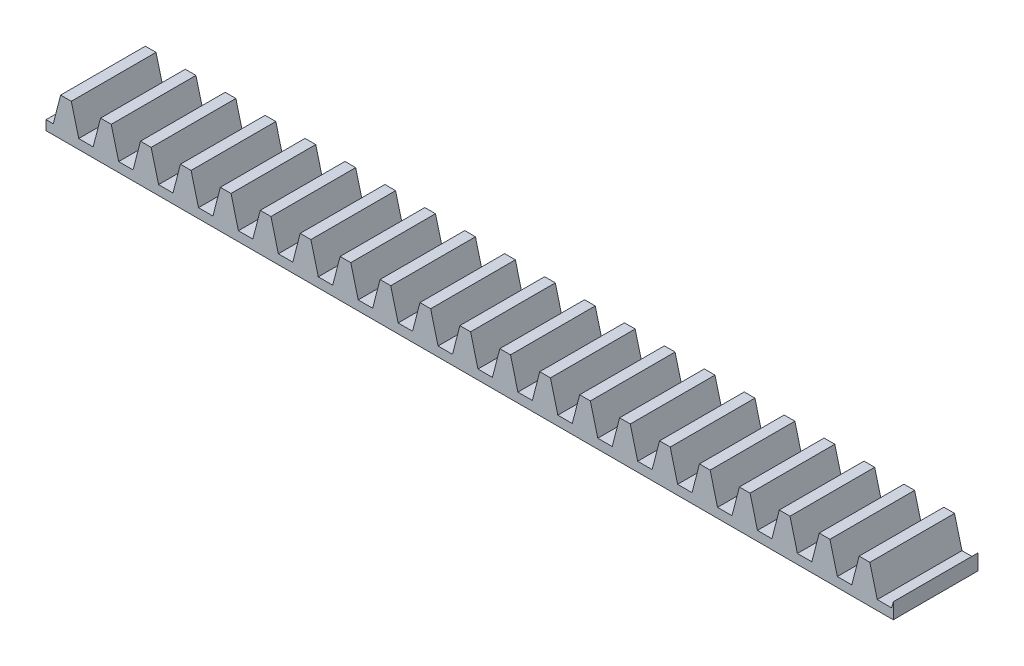
SolidWorks part; units mm, degrees
extrude "Blank" add sketch "BlankSke" against normal blind 10
sketch "BlankSke" plane through (0, 0, 0) normal (0, 0, 1) x (1, 0, 0)
  line L1 (0, 0) -> (100, 0)
  line L2 (0, 0) -> (0, 4.5)
  line L3 (0, 4.5) -> (100, 4.5)
  line L4 (100, 0) -> (100, 4.5)
  dimension "Length" = 100
  dimension "Blank_height" = 4.5
ref_plane "Plane1" through (0, 0, 0) normal (0, 0, 1) x (1, 0, 0)
ref_plane "Plane2" through (0, 0, 0) normal (0, 1, 0) x (1, 0, 0)
ref_plane "Plane3" through (0, 0, 0) normal (1, 0, 0) x (0, 0, -1)
sketch "HoldingSke" plane through (0, 0, 0) normal (0, 1, 0) x (1, 0, 0)
  line L0 (0, 0) -> (0.0928, 0.6602)
  line L1 (-15, 0) -> (100, 0) construction
  line L2 (0, 0) -> (-2.1039, 2.3779)
  line L3 (0, 0) -> (-11.863, 4.5341)
  line L4 (0, 0) -> (7.9495, 3.3743)
  line L5 (0, 0) -> (-23.7986, -8.8762)
  line L6 (0, 0) -> (-10.5278, -7.1032)
  line L9 (-67.7845, 28.3722) -> (29.0302, 53.4102)
  line L10 (-76.2, 3.8779) -> (-73.2, 3.8779)
  line L11 (0, 0) -> (-10, 0)
  line L12 (-76.2, 101.6) -> (-76.147, 101.6)
  line L13 (24.9733, 27.94) -> (52.9518, 28.4284)
  line L14 (24.9733, 27.94) -> (24.9743, 27.94)
  line L15 (24.9733, 27.94) -> (100.4006, 29.5858)
  circle A0 centre (0, 0) radius 19.05
  circle A1 centre (0, 0) radius 1.5
  circle A2 centre (0, 0) radius 12.7
  dimension "MPH" = 3
  dimension "Diameter" = 38.1
  dimension "Num_teeth" = 23
  dimension "Pitch" = 0.6667
  dimension "Show_teeth" = 998
  dimension "Thickness" = 12.7
  dimension "Ap" = 14.5
  dimension "Pitch_height" = 3
  dimension "Width" = 10
  dimension "Backlash" = 0.053
  dimension "Addendum_fac" = 1
  dimension "Dedendum_fac" = 1.25
  dimension "Clearance_fac" = 0.25
  dimension "Dedendum_add" = 0.001
  dimension "Length" = 100
  dimension "Module" = 1.5
sketch "TooCutSkeIll" plane through (0, 0, 0) normal (0, 0, 1) x (1, 0, 0)
  line L0 (-1.7134, 4.455) -> (-0.9251, 1.4069)
  line L1 (-0.5611, 1.125) -> (0.5611, 1.125)
  line L2 (0.9251, 1.4069) -> (1.7134, 4.455)
  line L3 (100, 4.5) -> (0, 4.5) construction
  line L4 (0, 0) -> (0, 64.897) construction
  line L5 (-13.208, 3) -> (12.954, 3) construction
  line L6 (0, 0) -> (100, 0) construction
  line L7 (1.3371, 3) -> (1.3371, 48.7463) construction
  line L8 (-1.3371, 3) -> (-1.3371, 48.7463) construction
  line L9 (1.7715, 4.5) -> (1.7715, 4.5254)
  line L10 (-1.7715, 4.5) -> (-1.7715, 4.5254)
  line L11 (-1.7715, 4.5254) -> (1.7715, 4.5254)
  arc A0 (0.5611, 1.125) -> (0.9251, 1.4069) centre (0.5611, 1.501) ccw
  arc A1 (-0.9251, 1.4069) -> (-0.5611, 1.125) centre (-0.5611, 1.501) ccw
  arc A2 (1.7715, 4.5) -> (1.7134, 4.455) centre (1.7715, 4.44) ccw
  arc A3 (-1.7134, 4.455) -> (-1.7715, 4.5) centre (-1.7715, 4.44) ccw
  dimension "Pitch_height" = 3
  dimension "Addendum_plus" = 1.5254
  dimension "Pressure_angle" = 14.5
  dimension "Gap_width" = 2.6742
  dimension "Dedendum" = 1.875
extrude "ToothCutIll" [suppressed] cut sketch "TooCutSkeIll" against normal through all
sketch "TooCutSkeSim" plane through (0, 0, 0) normal (0, 0, 1) x (1, 0, 0)
  line L0 (0.8522, 1.125) -> (-0.8522, 1.125)
  line L1 (1.7316, 4.5254) -> (0.8522, 1.125)
  line L2 (0, 17.4625) -> (0, 53.467) construction
  line L3 (1.7316, 4.5254) -> (-1.7316, 4.5254)
  line L6 (-1.7316, 4.5254) -> (-0.8522, 1.125)
  line L9 (-1.3371, 3) -> (1.3371, 3) construction
  line L10 (0, 0) -> (100, 0) construction
  line L11 (1.3371, 3) -> (1.3371, 53.467) construction
  line L12 (-1.3371, 3) -> (-1.3371, 53.467) construction
  dimension "Pitch_height" = 3
  dimension "Addendum_plus" = 1.5254
  dimension "Pressure_angle" = 14.5
  dimension "Gap_width" = 2.6742
  dimension "Dedendum" = 1.875
extrude "ToothCutSim" cut sketch "TooCutSkeSim" against normal through all
pattern_linear "TeethCuts" count 22 spacing 4.7124 along (1, 0, 0) of "ToothCutIll", "ToothCutSim"
equation "' \"Module@HoldingSke\" = 6.35"
equation "' \"Num_teeth@HoldingSke\" = 12"
equation "' \"Ap@HoldingSke\" =  20"
equation "' \"Ap@HoldingSke\" = 20"
equation "' \"Width@HoldingSke\" = 0.25 * 25.4"
equation "' \"Show_teeth@HoldingSke\" = 500"
equation "' \"Backlash@HoldingSke\" = 0.009 * 25.4"
equation "' \"Addendum_fac@HoldingSke\" = 1.0"
equation "' \"Dedendum_fac@HoldingSke\" = 1.25"
equation "' \"Dedendum_add@HoldingSke\" = 0.00005 * 25.4"
equation "' \"Clearance_fac@HoldingSke\" = 0.25"
equation "' \"Pitch_height@HoldingSke\" = 1 * 25.4"
equation "' \"Length@HoldingSke\" = 4.71 * 25.4"
equation "\"Pitch@HoldingSke\" = 1 / \"Module@HoldingSke\""
equation "\"MPH@HoldingSke\" = \"Dedendum_fac@HoldingSke\" / \"Pitch@HoldingSke\" + 2 * \"Dedendum_add@HoldingSke\" + 0.002 * 25.4"
equation "\"MPH@HoldingSke\" = ((sgn( \"MPH@HoldingSke\" - \"Pitch_height@HoldingSke\")+1)*( \"MPH@HoldingSke\" - \"Pitch_height@HoldingSke\"))/2 + \"Pitch_height@HoldingSke\""
equation "\"Blank_height@BlankSke\" = \"Pitch_height@HoldingSke\" + \"Addendum_fac@HoldingSke\"  / \"Pitch@HoldingSke\" "
equation "\"Length@BlankSke\" =  \"Length@HoldingSke\""
equation "\"Face_width@Blank\" = \"Width@HoldingSke\""
equation "\"Pressure_angle@TooCutSkeIll\" = \"Ap@HoldingSke\""
equation "\"Addendum_plus@TooCutSkeIll\" =  \"Addendum_fac@HoldingSke\"  / \"Pitch@HoldingSke\" + 0.001 *25.4"
equation "\"Dedendum@TooCutSkeIll\" = \"Dedendum_fac@HoldingSke\"  / \"Pitch@HoldingSke\""
equation "\"Pitch_height@TooCutSkeIll\" =  \"MPH@HoldingSke\""
equation "\"Gap_width@TooCutSkeIll\" = 3.14159265 / 2 / \"Pitch@HoldingSke\" + 6 * \"Backlash@HoldingSke\""
equation "\"Pressure_angle@TooCutSkeSim\" = \"Ap@HoldingSke\""
equation "\"Addendum_plus@TooCutSkeSim\" =  \"Addendum_fac@HoldingSke\"  / \"Pitch@HoldingSke\" + 0.001 * 25.4"
equation "\"Dedendum@TooCutSkeSim\" = \"Dedendum_fac@HoldingSke\"  / \"Pitch@HoldingSke\""
equation "\"Pitch_height@TooCutSkeSim\" =  \"MPH@HoldingSke\""
equation "\"Gap_width@TooCutSkeSim\" = 3.14159265 / 2 / \"Pitch@HoldingSke\" + 6 * \"Backlash@HoldingSke\""
equation "\"Root_fillet@TooCutSkeIll\" = \"Clearance_fac@HoldingSke\" / \"Pitch@HoldingSke\" + \"Dedendum_add@HoldingSke\""
equation "\"Break_rad@TooCutSkeIll\" = 0.02 / \"Pitch@HoldingSke\" * 2"
equation "\"Linear_pitch@TeethCuts\" = 3.14159265 / \"Pitch@HoldingSke\""
equation "\"Num_teeth@HoldingSke\" = int( ( \"Length@HoldingSke\" + 0 ) / (3.14159265 / \"Pitch@HoldingSke\")) + 0.9999  + 1"
equation " \"Num_teeth@TeethCuts\" = int( \"Show_teeth@HoldingSke\" ) + 1"
equation " \"Num_teeth@TeethCuts\" = ((sgn( \"Num_teeth@TeethCuts\" - \"Num_teeth@HoldingSke\" )-1)*( \"Num_teeth@TeethCuts\" - \"Num_teeth@HoldingSke\" ))/-2+ \"Num_teeth@HoldingSke\""
equation " \"Num_teeth@TeethCuts\" = ((sgn( \"Num_teeth@TeethCuts\" - 2.0)+1)*( \"Num_teeth@TeethCuts\" - 2.0))/2 +2.0"
